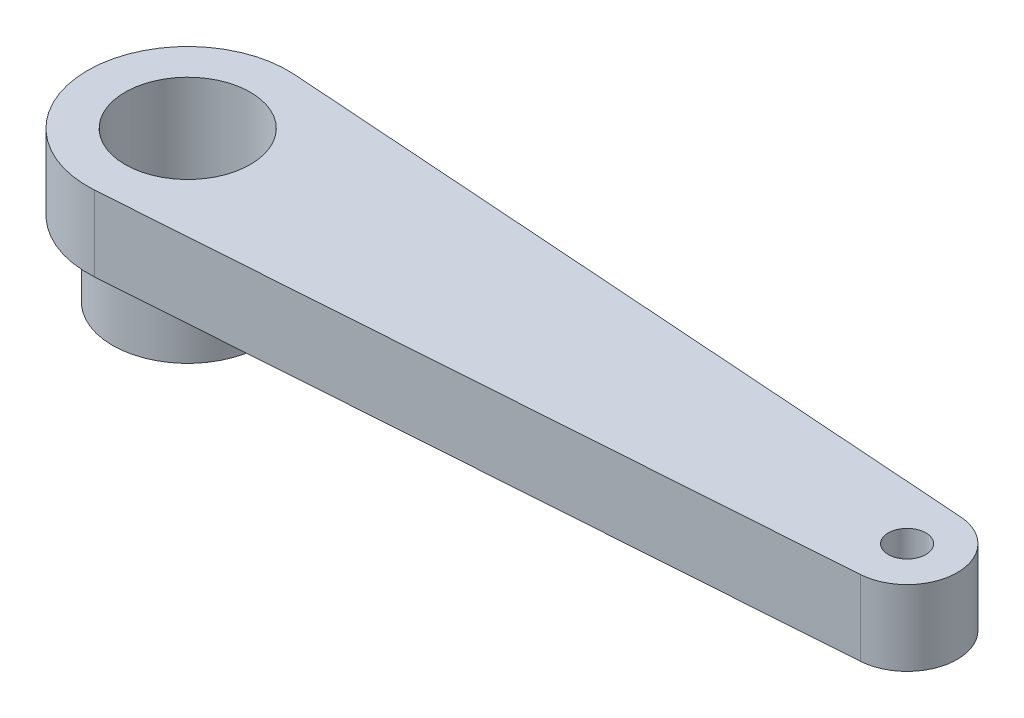
SolidWorks part; units mm, degrees
ref_plane "Front Plane" through (0, 0, 0) normal (0, 0, 1) x (1, 0, 0)
ref_plane "Top Plane" through (0, 0, 0) normal (0, 1, 0) x (1, 0, 0)
ref_plane "Right Plane" through (0, 0, 0) normal (1, 0, 0) x (0, 0, -1)
sketch "Sketch1" plane through (0, 0, 0) normal (0, 1, 0) x (1, 0, 0)
  line L0 (-31.8456, 0) -> (31.8456, 0) construction
  line L1 (0.2787, 3.9903) -> (28.8394, 1.9951)
  line L2 (0.2787, -3.9903) -> (28.8394, -1.9951)
  arc A0 (0.2787, 3.9903) -> (0.2787, -3.9903) centre (0, 0) ccw
  arc A1 (28.8394, -1.9951) -> (28.8394, 1.9951) centre (28.7, 0) ccw
  circle A2 centre (0, 0) radius 2.5
  circle A3 centre (28.7, 0) radius 0.75
  dimension "D2" = 5
  dimension "D3" = 4
  dimension "D4" = 2
  dimension "D5" = 1.5
  dimension "D1" = 28.7
extrude "Boss-Extrude1" add sketch "Sketch1" along normal blind 3
sketch "Sketch2" plane through (0, 3, 0) normal (0, 1, 0) x (1, 0, 0)
  circle A0 centre (0, 0) radius 3
  circle A1 centre (0, 0) radius 2.5
  dimension "5" = 5
  dimension "D2" = 6
extrude "Boss-Extrude2" add sketch "Sketch2" against normal blind 3 from surface at -3 starting at face at (13.9545, 0, 0)
